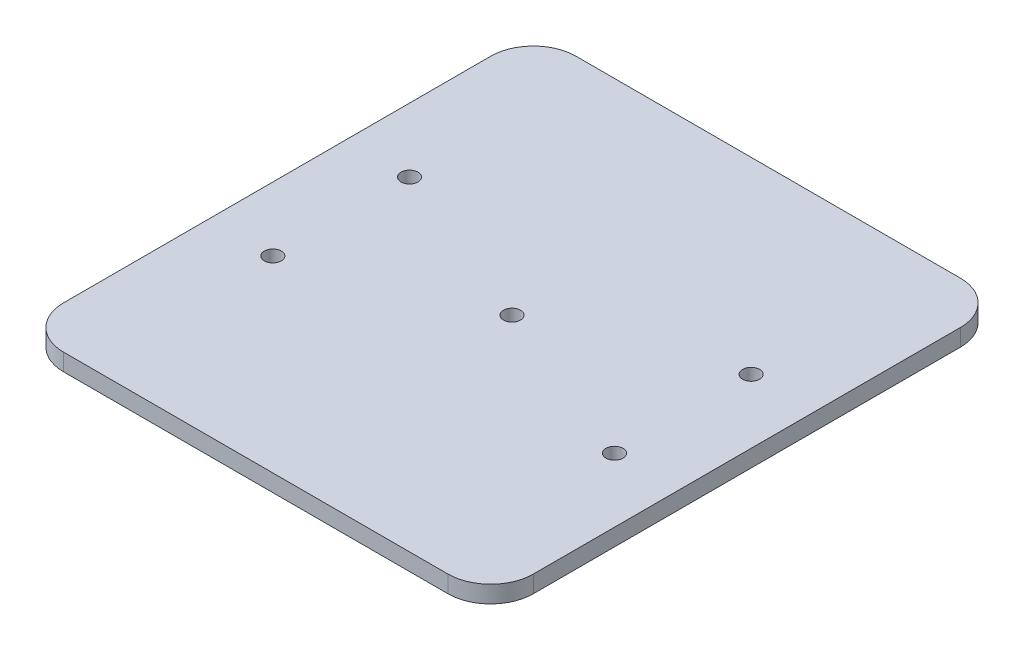
SolidWorks part; units mm, degrees
ref_plane "Front Plane" through (0, 0, 0) normal (0, 0, 1) x (1, 0, 0)
ref_plane "Top Plane" through (0, 0, 0) normal (0, 1, 0) x (1, 0, 0)
ref_plane "Right Plane" through (0, 0, 0) normal (1, 0, 0) x (0, 0, -1)
sketch "Sketch1" plane through (0, 0, 0) normal (0, 1, 0) x (1, 0, 0)
  line L1 (-36.8009, 29.8578) -> (8.1991, 29.8578)
  line L2 (-41.8009, 24.8578) -> (-41.8009, -25.1422)
  line L3 (-36.8009, -30.1422) -> (8.1991, -30.1422)
  line L4 (13.1991, 24.8578) -> (13.1991, -25.1422)
  arc A0 (8.1991, -30.1422) -> (13.1991, -25.1422) centre (8.1991, -25.1422) ccw
  arc A1 (-41.8009, -25.1422) -> (-36.8009, -30.1422) centre (-36.8009, -25.1422) ccw
  arc A2 (8.1991, 29.8578) -> (13.1991, 24.8578) centre (8.1991, 24.8578) cw
  arc A3 (-41.8009, 24.8578) -> (-36.8009, 29.8578) centre (-36.8009, 24.8578) cw
  circle A4 centre (-34.3009, 7.8578) radius 1
  circle A5 centre (-34.3009, -8.1422) radius 1
  circle A6 centre (-14.3009, -0.1422) radius 1
  point P8 (-41.8009, -30.1422)
  point P11 (13.1991, 29.8578)
  point P14 (-41.8009, 29.8578)
  dimension "D3" = 5
  dimension "D4" = 7.5
  dimension "D6" = 22
  dimension "D7" = 30
  dimension "D1" = 60
  dimension "D2" = 55
  dimension "D5" = 22
  dimension "D8" = 27.5
extrude "Boss-Extrude1" add sketch "Sketch1" along normal blind 2
sketch "Sketch2" plane through (0, 0, 0) normal (0, 1, 0) x (1, 0, 0)
  line L0 (13.1991, -25.1422) -> (13.1991, 24.8578) construction
  line L1 (8.1991, 29.8578) -> (-36.8009, 29.8578) construction
  line L2 (-36.8009, -30.1422) -> (8.1991, -30.1422) construction
  circle A0 centre (5.6991, 7.8578) radius 1
  circle A1 centre (5.6991, -8.1422) radius 1
  dimension "D1" = 7.5
  dimension "D2" = 22
  dimension "D3" = 22
extrude "Cut-Extrude1" cut sketch "Sketch2" along normal blind 9
